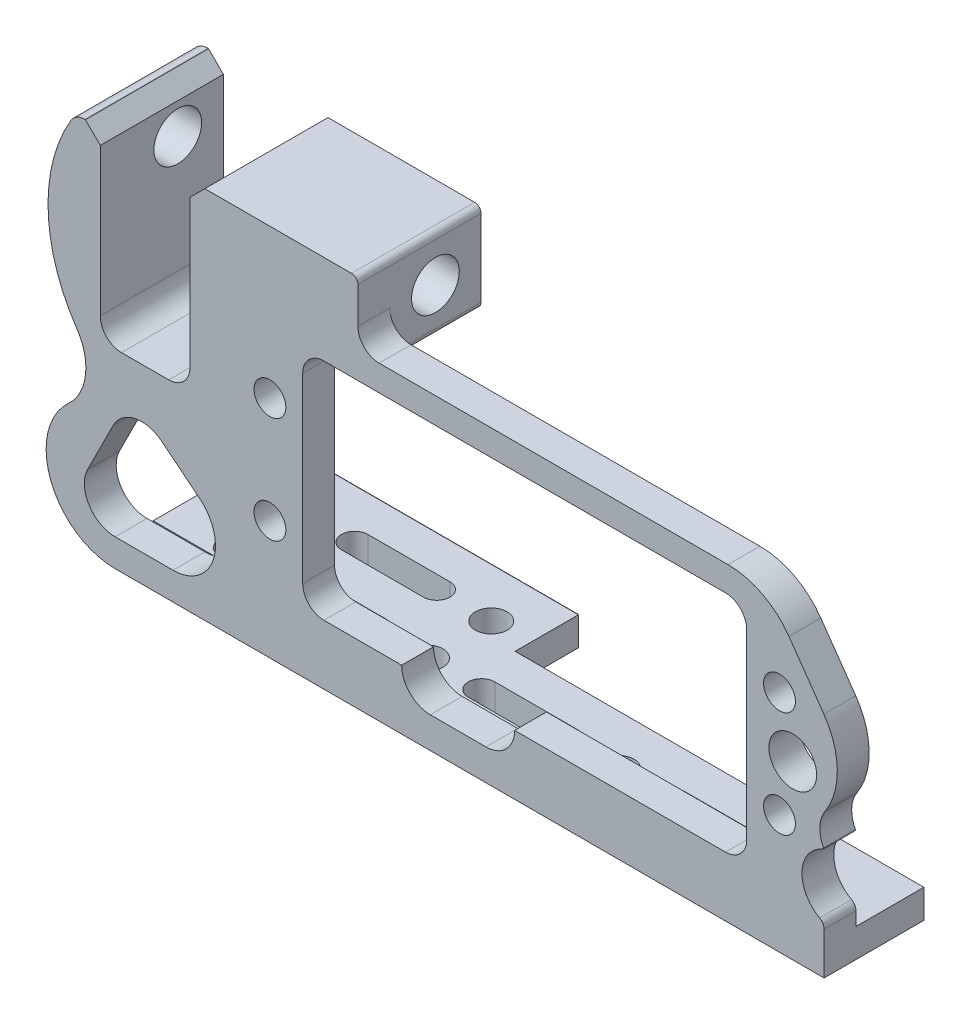
SolidWorks part; units mm, degrees
ref_plane "前视基准面" through (0, 0, 0) normal (0, 0, 1) x (1, 0, 0)
ref_plane "上视基准面" through (0, 0, 0) normal (0, 1, 0) x (1, 0, 0)
ref_plane "右视基准面" through (0, 0, 0) normal (1, 0, 0) x (0, 0, -1)
other "Configuration Table"
ref_plane "基准面1" through (0, 0, -7.725) normal (0, 0, -1) x (-1, 0, 0)
sketch "草图1" plane through (0, 0, -7.725) normal (0, 0, -1) x (-1, 0, 0)
  line L0 (33.1, 4.5) -> (24.8243, 4.5)
  line L1 (25.7249, 9.7195) -> (29.3009, 12.5896)
  line L2 (33.859, 11.5975) -> (36.2697, 6.8026)
  line L3 (33.6787, 2.6) -> (33.1, 2.6)
  line L4 (33.1, 2.6) -> (33.1, 4.5)
  line L5 (-33.1, 4.5) -> (-33.1, 0)
  line L6 (-33.1, 0) -> (33.6787, 0)
  line L7 (37.38, 35.225) -> (10.81, 35.225)
  line L8 (10.81, 35.225) -> (10.81, 29.2)
  line L9 (10.81, 29.2) -> (-27.6994, 29.2)
  line L10 (-27.6994, 29.2) -> (-33.0805, 21.515)
  arc A0 (24.8243, 4.5) -> (25.7249, 9.7195) centre (28.2287, 6.6) cw
  arc A1 (29.3009, 12.5896) -> (33.859, 11.5975) centre (31.1787, 10.25) cw
  arc A2 (36.2697, 6.8026) -> (33.6787, 2.6) centre (33.6787, 5.5) cw
  arc A3 (-33.1, 10.5) -> (-33.1, 4.5) centre (-34.2136, 7.5) cw
  arc A4 (33.6787, 0) -> (38.0616, 11.3) centre (33.6787, 6.5) ccw
  arc A5 (38.0616, 11.3) -> (37.2993, 17.8052) centre (41.433, 14.9924) cw
  arc A6 (37.2993, 17.8052) -> (37.38, 35.225) centre (24.4109, 26.575) ccw
  arc A7 (-33.0805, 21.515) -> (-33.1926, 13.65) centre (-27.3464, 17.5) ccw
  arc A8 (-33.1926, 13.65) -> (-33.1, 10.5) centre (-35.6981, 12) cw
extrude "凸台-拉伸1" add sketch "草图1" against normal blind 15.45
sketch "草图2" plane through (0, 0, 7.725) normal (0, 0, 1) x (1, 0, 0)
  line L0 (-33.1, 2.7) -> (-33.1, 2.6)
  line L1 (-33.1, 2.6) -> (-28.2287, 2.6)
  line L2 (-24.8243, 4.5) -> (-33.1, 4.5)
  line L3 (-33.1, 4.5) -> (-33.1, 2.7)
  arc A0 (-28.2287, 2.6) -> (-24.8243, 4.5) centre (-28.2287, 6.6) ccw
extrude "切除-拉伸1" cut sketch "草图2" against normal blind 3
sketch "草图3" plane through (0, 0, -7.725) normal (0, 0, -1) x (-1, 0, 0)
  line L0 (37.38, 35.225) -> (10.81, 35.225)
  line L1 (10.81, 35.225) -> (10.81, 29.2)
  line L2 (10.81, 29.2) -> (-27.6994, 29.2)
  line L3 (-27.6994, 29.2) -> (-33.0805, 21.515)
  line L4 (-33.1, 4.5) -> (24.8243, 4.5)
  line L5 (25.7249, 9.7195) -> (29.3009, 12.5896)
  line L6 (33.859, 11.5975) -> (36.2697, 6.8026)
  line L7 (33.6787, 2.6) -> (33.1, 2.6)
  line L8 (33.1, 2.6) -> (33.1, 0)
  line L9 (33.1, 0) -> (33.6787, 0)
  arc A0 (33.6787, 0) -> (38.0616, 11.3) centre (33.6787, 6.5) ccw
  arc A1 (38.0616, 11.3) -> (37.2993, 17.8052) centre (41.433, 14.9924) cw
  arc A2 (37.2993, 17.8052) -> (37.38, 35.225) centre (24.4109, 26.575) ccw
  arc A3 (-33.0805, 21.515) -> (-33.1926, 13.65) centre (-27.3464, 17.5) ccw
  arc A4 (-33.1926, 13.65) -> (-33.1, 10.5) centre (-35.6981, 12) cw
  arc A5 (-33.1, 10.5) -> (-33.1, 4.5) centre (-34.2136, 7.5) cw
  arc A6 (24.8243, 4.5) -> (25.7249, 9.7195) centre (28.2287, 6.6) cw
  arc A7 (29.3009, 12.5896) -> (33.859, 11.5975) centre (31.1787, 10.25) cw
  arc A8 (36.2697, 6.8026) -> (33.6787, 2.6) centre (33.6787, 5.5) cw
extrude "切除-拉伸2" cut sketch "草图3" against normal blind 3.85
ref_plane "基准面2" through (0, 5.625, 0) normal (0, -1, 0) x (1, 0, 0)
sketch "草图4" plane through (0, 5.625, 0) normal (0, -1, 0) x (1, 0, 0)
  line L0 (-16.01, -3.875) -> (25.81, -3.875)
  line L1 (25.81, -3.875) -> (25.81, 7.725)
  line L2 (25.81, 7.725) -> (-16.01, 7.725)
  line L3 (-16.01, 7.725) -> (-16.01, -3.875)
extrude "切除-拉伸3" cut sketch "草图4" against normal blind 21.15
sketch "草图5" plane through (0, 0, -3.875) normal (0, 0, -1) x (-1, 0, 0)
  line L0 (-33.1, 4.5) -> (24.8243, 4.5)
  line L1 (25.7249, 9.7195) -> (29.3009, 12.5896)
  line L2 (33.859, 11.5975) -> (36.2697, 6.8026)
  line L3 (33.6787, 2.6) -> (33.1, 2.6)
  line L4 (33.1, 2.6) -> (33.1, 0)
  line L5 (33.1, 0) -> (33.6787, 0)
  line L6 (36.4923, 14.225) -> (31.8022, 14.225)
  line L7 (25.2221, 26.775) -> (16.01, 26.775)
  line L8 (16.01, 26.775) -> (16.01, 5.625)
  line L9 (16.01, 5.625) -> (-25.81, 5.625)
  line L10 (-25.81, 5.625) -> (-25.81, 26.775)
  line L11 (-25.81, 26.775) -> (10.81, 26.775)
  line L12 (10.81, 26.775) -> (10.81, 29.2)
  line L13 (10.81, 29.2) -> (-27.6994, 29.2)
  line L14 (-27.6994, 29.2) -> (-33.0805, 21.515)
  arc A0 (24.8243, 4.5) -> (25.7249, 9.7195) centre (28.2287, 6.6) cw
  arc A1 (29.3009, 12.5896) -> (33.859, 11.5975) centre (31.1787, 10.25) cw
  arc A2 (36.2697, 6.8026) -> (33.6787, 2.6) centre (33.6787, 5.5) cw
  arc A3 (33.6787, 0) -> (38.0616, 11.3) centre (33.6787, 6.5) ccw
  arc A4 (38.0616, 11.3) -> (36.4923, 14.225) centre (41.433, 14.9924) cw
  arc A5 (31.8022, 14.225) -> (25.2221, 26.775) centre (31.8022, 22.225) cw
  arc A6 (-33.0805, 21.515) -> (-33.1926, 13.65) centre (-27.3464, 17.5) ccw
  arc A7 (-33.1926, 13.65) -> (-33.1, 10.5) centre (-35.6981, 12) cw
  arc A8 (-33.1, 10.5) -> (-33.1, 4.5) centre (-34.2136, 7.5) cw
extrude "切除-拉伸4" cut sketch "草图5" against normal blind 8.6
sketch "草图6" plane through (0, 4.5, 0) normal (0, 1, 0) x (-1, 0, 0)
  line L0 (-33.1, 4.725) -> (-33.1, -7.725)
  line L1 (-33.1, -7.725) -> (33.1, -7.725)
  line L2 (33.1, -7.725) -> (33.1, 4.725)
  line L3 (33.1, 4.725) -> (27.3399, 4.725)
  line L4 (27.3399, 4.725) -> (-33.1, 4.725)
extrude "切除-拉伸5" cut sketch "草图6" against normal blind 1.8
sketch "草图7" plane through (0, 0, 4.725) normal (0, 0, -1) x (-1, 0, 0)
  line L0 (6.69, 5.625) -> (-3.95, 5.625)
  line L1 (-1.25, 2.925) -> (3.99, 2.925)
  arc A0 (-3.95, 5.625) -> (-1.25, 2.925) centre (-1.25, 5.625) ccw
  arc A1 (3.99, 2.925) -> (6.69, 5.625) centre (3.99, 5.625) ccw
extrude "切除-拉伸6" cut sketch "草图7" against normal through all
sketch "草图8" plane through (0, 0, 0) normal (0, -1, 0) x (1, 0, 0)
  line L0 (33.1, -1.675) -> (-5.4, -1.675)
  line L1 (-5.4, -1.675) -> (-5.4, -7.725)
  line L2 (-5.4, -7.725) -> (33.1, -7.725)
  line L3 (33.1, -7.725) -> (33.1, -1.675)
extrude "切除-拉伸7" cut sketch "草图8" against normal through all
sketch "草图9" plane through (0, 0, 7.725) normal (0, 0, 1) x (1, 0, 0)
  line L0 (-26.63, 35.225) -> (-36.48, 35.225)
  line L1 (-36.48, 35.225) -> (-35.08, 33.825)
  line L2 (-35.08, 33.825) -> (-35.08, 17.925)
  line L3 (-35.08, 17.925) -> (-26.63, 17.925)
  line L4 (-26.63, 17.925) -> (-26.63, 35.225)
extrude "切除-拉伸8" cut sketch "草图9" against normal through all
sketch "草图10" plane through (0, 2.7, 0) normal (0, 1, 0) x (-1, 0, 0)
  line L0 (3.865, 4.275) -> (-3.865, 4.275)
  line L1 (-3.865, 1.775) -> (3.865, 1.775)
  arc A0 (-3.865, 4.275) -> (-3.865, 1.775) centre (-3.865, 3.025) ccw
  arc A1 (3.865, 1.775) -> (3.865, 4.275) centre (3.865, 3.025) ccw
extrude "切除-拉伸9" cut sketch "草图10" against normal through all
sketch "草图11" plane through (0, 2.7, 0) normal (0, 1, 0) x (-1, 0, 0)
  line L0 (-14.135, 4.275) -> (-21.865, 4.275)
  line L1 (-21.865, 1.775) -> (-14.135, 1.775)
  arc A0 (-21.865, 4.275) -> (-21.865, 1.775) centre (-21.865, 3.025) ccw
  arc A1 (-14.135, 1.775) -> (-14.135, 4.275) centre (-14.135, 3.025) ccw
extrude "切除-拉伸10" cut sketch "草图11" against normal through all
sketch "草图12" plane through (0, 2.7, 0) normal (0, 1, 0) x (-1, 0, 0)
  line L0 (14.135, -4.275) -> (21.865, -4.275)
  line L1 (21.865, -1.775) -> (14.135, -1.775)
  arc A0 (14.135, -1.775) -> (14.135, -4.275) centre (14.135, -3.025) ccw
  arc A1 (21.865, -4.275) -> (21.865, -1.775) centre (21.865, -3.025) ccw
extrude "切除-拉伸11" cut sketch "草图12" against normal through all
sketch "草图13" plane through (0, 0, 0) normal (0, -1, 0) x (1, 0, 0)
  line L0 (-14.135, 4.275) -> (-21.865, 4.275)
  line L1 (-21.865, 1.775) -> (-14.135, 1.775)
  arc A0 (-21.865, 4.275) -> (-21.865, 1.775) centre (-21.865, 3.025) ccw
  arc A1 (-14.135, 1.775) -> (-14.135, 4.275) centre (-14.135, 3.025) ccw
extrude "切除-拉伸12" cut sketch "草图13" against normal up to next
hole_wizard "Ø4.5 (4.5) 直径孔1" positions "草图15" profile "草图14" hole size "Ø4.5" standard "ANSI Metric"
sketch "草图15" plane through (0, 0, 7.725) normal (0, 0, 1) x (1, 0, 0)
  point P0 (30.15, 16.2)
sketch "草图14" plane through (30.15, 16.2, 7.725) normal (1, 0, 0) x (0, -1, 0)
  line L0 (0, 0) -> (0, 15.45)
  line L1 (0, 15.45) -> (2.25, 15.45)
  line L2 (2.25, 15.45) -> (2.25, 0)
  line L5 (2.25, 0) -> (0, 0)
  line L11 (0, -6.35) -> (0, 107.95) construction
  dimension "通孔孔直径" = 4.5
  dimension "通孔孔深度" = 15.45
hole_wizard "Ø3.0 (3) 直径孔1" positions "草图17" profile "草图16" hole size "Ø3.0" standard "ANSI Metric"
sketch "草图17" plane through (0, 0, 7.725) normal (0, 0, 1) x (1, 0, 0)
  point P0 (-19.1, 11.2)
  point P1 (28.9, 11.2)
  point P2 (-19.1, 21.2)
  point P3 (28.9, 21.2)
sketch "草图16" plane through (-19.1, 11.2, 7.725) normal (1, 0, 0) x (0, -1, 0)
  line L0 (0, 0) -> (0, 15.45)
  line L1 (0, 15.45) -> (1.5, 15.45)
  line L2 (1.5, 15.45) -> (1.5, 0)
  line L5 (1.5, 0) -> (0, 0)
  line L11 (0, -6.35) -> (0, 107.95) construction
  dimension "通孔孔直径" = 3
  dimension "通孔孔深度" = 15.45
hole_wizard "Ø4.5 (4.5) 直径孔2" positions "草图19" profile "草图18" hole size "Ø4.5" standard "ANSI Metric"
sketch "草图19" plane through (-10.81, 0, 0) normal (1, 0, 0) x (0, 0, -1)
  point P0 (-0.425, 30.925)
sketch "草图18" plane through (-10.81, 30.925, 0.425) normal (0, 1, 0) x (0, 0, -1)
  line L0 (0, 0) -> (0, 15.82)
  line L1 (0, 15.82) -> (2.25, 15.82)
  line L2 (2.25, 15.82) -> (2.25, 0)
  line L5 (2.25, 0) -> (0, 0)
  line L11 (0, -6.35) -> (0, 107.95) construction
  dimension "通孔孔直径" = 4.5
  dimension "通孔孔深度" = 15.82
hole_wizard "Ø3.0 (3) 直径孔2" positions "草图21" profile "草图20" hole size "Ø3.0" standard "ANSI Metric"
sketch "草图21" plane through (0, 0, 0) normal (0, -1, 0) x (-1, 0, 0)
  point P0 (-9, -3.025)
  point P1 (9, -3.025)
  point P2 (9, 3.025)
  point P3 (-27, -3.025)
sketch "草图20" plane through (9, 0, 3.025) normal (1, 0, 0) x (0, 0, -1)
  line L0 (0, 0) -> (0, 35.225)
  line L1 (0, 35.225) -> (1.5, 35.225)
  line L2 (1.5, 35.225) -> (1.5, 0)
  line L5 (1.5, 0) -> (0, 0)
  line L11 (0, -6.35) -> (0, 107.95) construction
  dimension "通孔孔直径" = 3
  dimension "通孔孔深度" = 35.225
hole_wizard "Ø3.0 (3) 直径孔3" positions "草图23" profile "草图22" hole size "Ø3.0" standard "ANSI Metric"
sketch "草图23" plane through (0, 0, 0) normal (0, -1, 0) x (-1, 0, 0)
  point P0 (27, -3.025)
  point P1 (27, 3.025)
sketch "草图22" plane through (-27, 0, 3.025) normal (1, 0, 0) x (0, 0, -1)
  line L0 (0, 0) -> (0, 2.7)
  line L1 (0, 2.7) -> (1.5, 2.7)
  line L2 (1.5, 2.7) -> (1.5, 0)
  line L5 (1.5, 0) -> (0, 0)
  line L11 (0, -6.35) -> (0, 107.95) construction
  dimension "通孔孔直径" = 3
  dimension "通孔孔深度" = 2.7
hole_wizard "Ø4.5 (4.5) 直径孔3" positions "草图25" profile "草图24" hole size "Ø4.5" standard "ANSI Metric"
sketch "草图25" plane through (-35.08, 0, 0) normal (1, 0, 0) x (0, 0, -1)
  point P0 (-0.425, 30.925)
sketch "草图24" plane through (-35.08, 30.925, 0.425) normal (0, 1, 0) x (0, 0, -1)
  line L0 (0, 0) -> (0, 5.0987)
  line L1 (0, 5.0987) -> (2.25, 5.0987)
  line L2 (2.25, 5.0987) -> (2.25, 0)
  line L5 (2.25, 0) -> (0, 0)
  line L11 (0, -6.35) -> (0, 107.95) construction
  dimension "通孔孔直径" = 4.5
  dimension "通孔孔深度" = 5.0987
chamfer "倒角1" distance 1.4 angle 45 1 edges at (-26.63, 35.225, 1.925)
fillet "圆角1" radius 0.1 5 edges at (-5.4, 1.35, -7.725) (-19.25, 0, -7.725) (-19.25, 2.7, -7.725) (-33.1, 1.35, -7.725) (33.1, 10.5, 6.225)
fillet "圆角2" radius 0.6 3 edges at (-10.81, 35.225, 1.925) (-36.4923, 14.225, 0.425) (-10.81, 26.775, 0.425)
fillet "圆角3" radius 0.8 1 edges at (33.1, 4.5, 6.225)
fillet "圆角4" radius 1.5 1 edges at (-37.38, 35.225, 1.925)
fillet "圆角5" radius 2 7 edges at (-10.81, 29.2, 6.225) (25.81, 5.625, 6.225) (-26.63, 17.925, 1.925) (-16.01, 5.625, 6.225) (-16.01, 26.775, 6.225) (25.81, 26.775, 6.225) (-35.08, 17.925, 1.925)
fillet "圆角6" radius 5 1 edges at (-25.2221, 26.775, 0.425)
fillet "圆角7" radius 7 1 edges at (27.6994, 29.2, 6.225)
